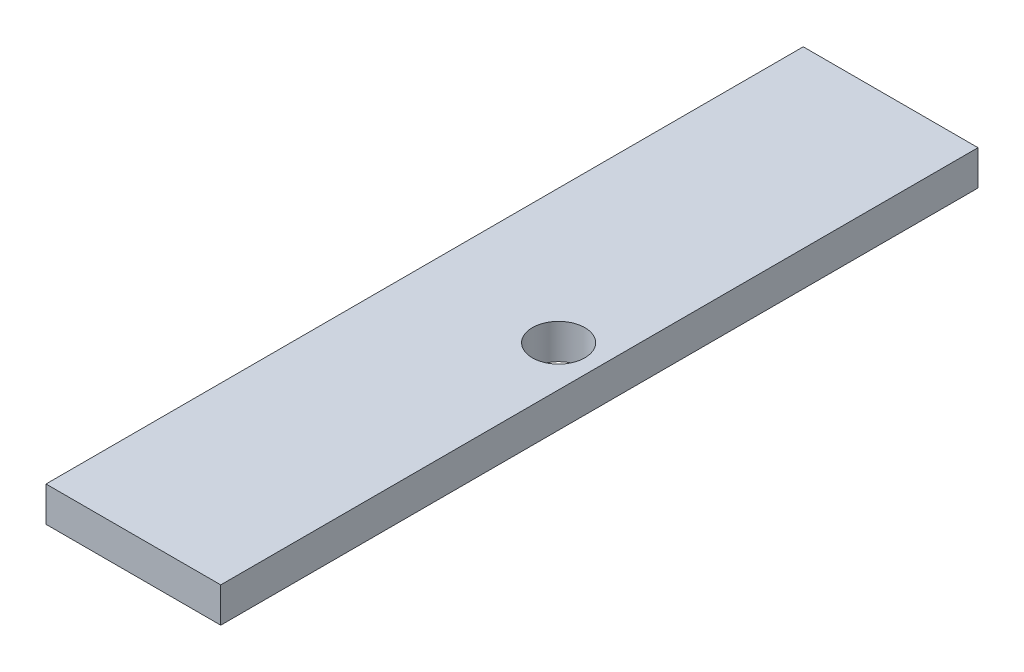
SolidWorks part; units mm, degrees
material "Alu Künz"
ref_plane "Ebene vorne" through (0, 0, 0) normal (0, 0, 1) x (1, 0, 0)
ref_plane "Ebene oben" through (0, 0, 0) normal (0, 1, 0) x (1, 0, 0)
ref_plane "Ebene rechts" through (0, 0, 0) normal (1, 0, 0) x (0, 0, -1)
sketch "Skizze1" plane through (0, 0, 0) normal (0, 0, 1) x (1, 0, 0)
  line L7 (-15, -3) -> (15, 3) construction
  line L8 (-15, 3) -> (15, 3)
  line L9 (-15, 3) -> (-15, -3)
  line L10 (-15, -3) -> (15, -3)
  line L11 (15, 3) -> (15, -3)
  dimension "D1" = 6
  dimension "D2" = 30
extrude "Aufsatz-Linear austragen1" add sketch "Skizze1" along normal mid plane 130
sketch "Sketch1" plane through (0, 0, 0) normal (0, 1, 0) x (1, 0, 0)
  line L0 (0, 0) -> (8, 0) construction
  line L1 (15, -65) -> (15, 65) construction
  circle A0 centre (8, 0) radius 4.5
  dimension "D1" = 9
  dimension "D2" = 7
extrude "Cut-Extrude1" cut sketch "Sketch1" against normal through all both and the other way through all
